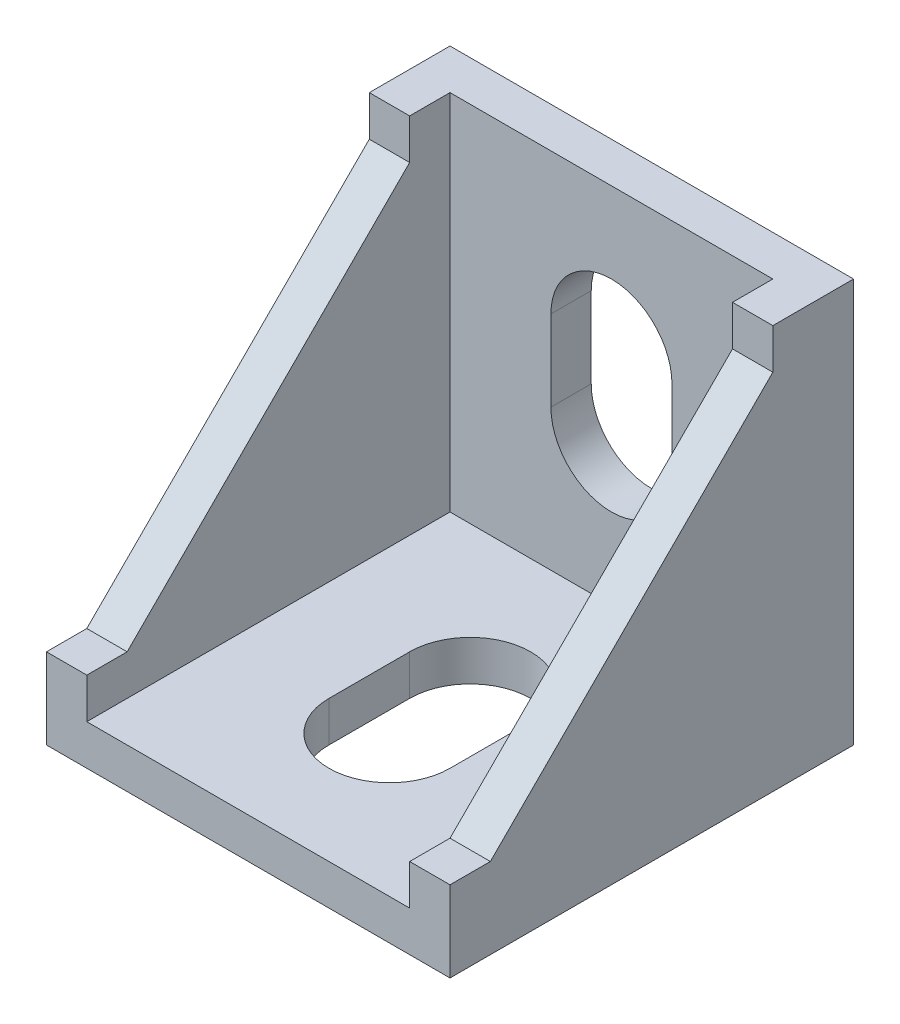
SolidWorks part; units mm, degrees
ref_plane "Front Plane" through (0, 0, 0) normal (0, 0, 1) x (1, 0, 0)
ref_plane "Top Plane" through (0, 0, 0) normal (0, 1, 0) x (1, 0, 0)
ref_plane "Right Plane" through (0, 0, 0) normal (1, 0, 0) x (0, 0, -1)
sketch "Sketch2" plane through (0, 0, 0) normal (0, 1, 0) x (1, 0, 0)
  line L1 (-10, -10) -> (10, -10)
  line L2 (-10, -10) -> (-10, 10)
  line L3 (-10, 10) -> (10, 10)
  line L4 (10, -10) -> (10, 10)
  line L5 (-10, -10) -> (10, 10) construction
  line L6 (-10, 10) -> (10, -10) construction
  point P0 (0, 0)
  dimension "D1" = 20
  dimension "D2" = 20
extrude "Boss-Extrude1" add sketch "Sketch2" along normal blind 2
sketch "Sketch4" plane through (0, 0, -10) normal (0, 0, -1) x (-1, 0, 0)
  line L1 (10, 0) -> (-10, 0)
  line L2 (10, 0) -> (10, 20)
  line L3 (10, 20) -> (-10, 20)
  line L4 (-10, 0) -> (-10, 20)
  dimension "D1" = 20
extrude "Boss-Extrude2" add sketch "Sketch4" against normal blind 2
sketch "Sketch5" plane through (-10, 0, 0) normal (-1, 0, 0) x (0, 0, 1)
  line L0 (-6, 18) -> (8, 4)
  line L1 (-8, 20) -> (-6, 20)
  line L2 (-8, 20) -> (-8, 2)
  line L4 (-6, 20) -> (-6, 18)
  line L5 (10, 2) -> (-8, 2)
  line L6 (10, 2) -> (10, 4)
  line L7 (10, 4) -> (8, 4)
  line L9 (-8, 2) -> (-8, 20) construction
  dimension "D1" = 2
  dimension "D2" = 2
extrude "Boss-Extrude3" add sketch "Sketch5" against normal blind 2 contours L0 L7 L6 L5 L2 L1 L4
mirror "Mirror1" about plane through (0, 0, 0) normal (1, 0, 0) of "Boss-Extrude3"
sketch "Sketch6" plane through (0, 2, 0) normal (0, 1, 0) x (1, 0, 0)
  line L0 (0, 1) -> (0, -3) construction
  line L1 (3, 1) -> (3, -3)
  line L2 (-3, 1) -> (-3, -3)
  line L3 (0, 8) -> (0, -10) construction
  line L4 (-8, 8) -> (8, 8) construction
  line L5 (-8, -10) -> (8, -10) construction
  arc A0 (3, 1) -> (-3, 1) centre (0, 1) ccw
  arc A1 (-3, -3) -> (3, -3) centre (0, -3) ccw
  point P3 (0, -1)
  point P9 (0, 4)
  point P10 (0, -6)
  dimension "D1" = 6
  dimension "D2" = 10
extrude "Cut-Extrude1" cut sketch "Sketch6" against normal through all both and the other way through all
sketch "Sketch7" plane through (0, 0, -8) normal (0, 0, 1) x (1, 0, 0)
  line L0 (0, 13) -> (0, 9) construction
  line L1 (3, 13) -> (3, 9)
  line L2 (-3, 13) -> (-3, 9)
  line L3 (0, 20) -> (0, 2) construction
  line L4 (-8, 20) -> (8, 20) construction
  line L5 (-8, 2) -> (8, 2) construction
  arc A0 (3, 13) -> (-3, 13) centre (0, 13) ccw
  arc A1 (-3, 9) -> (3, 9) centre (0, 9) ccw
  point P3 (0, 11)
  point P17 (0, 16)
  point P18 (0, 6)
  dimension "D1" = 6
  dimension "D2" = 10
extrude "Cut-Extrude2" cut sketch "Sketch7" against normal through all both and the other way through all
